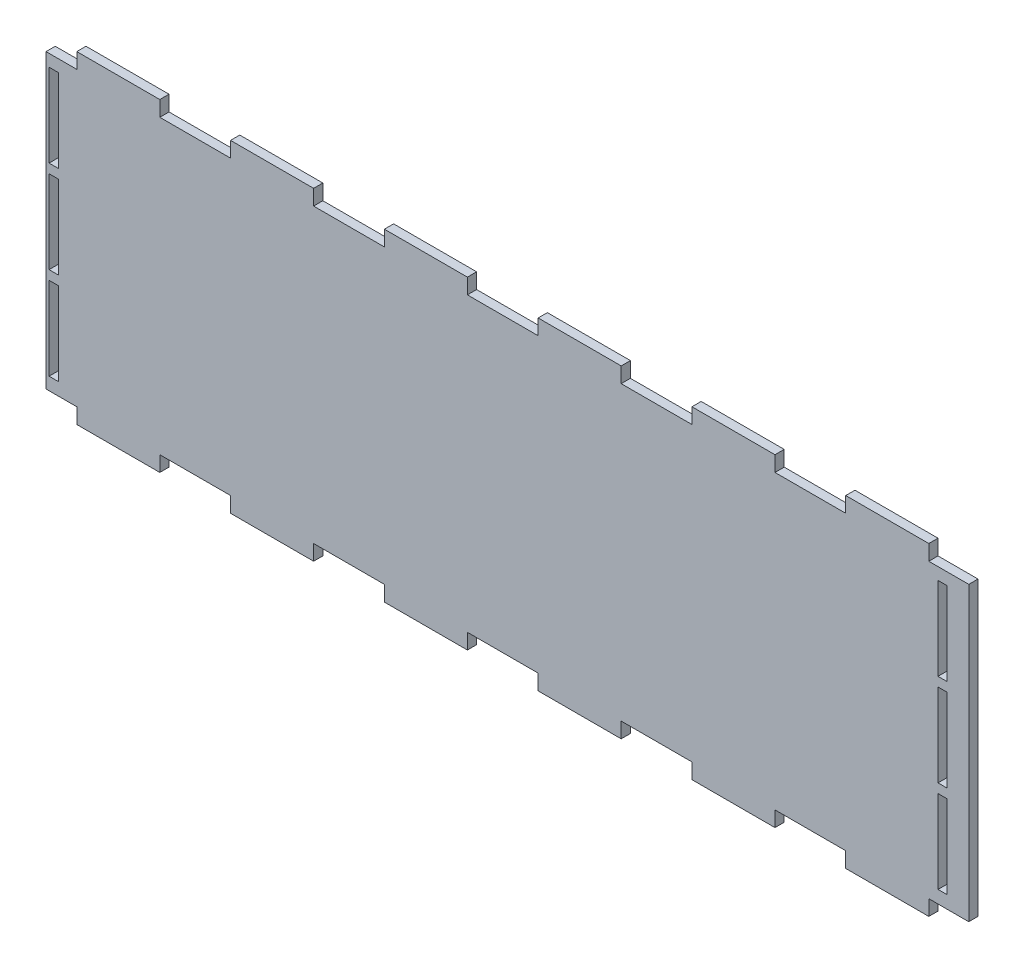
SolidWorks part; units mm, degrees
ref_plane "Plan de face" through (0, 0, 0) normal (0, 0, 1) x (1, 0, 0)
ref_plane "Plan de dessus" through (0, 0, 0) normal (0, 1, 0) x (1, 0, 0)
ref_plane "Plan de droite" through (0, 0, 0) normal (1, 0, 0) x (0, 0, -1)
sketch "Sketch1" plane through (0, 0, 0) normal (0, 0, 1) x (1, 0, 0)
  line L0 (-90, 47.5) -> (-90, 52.5)
  line L1 (150, -47.5) -> (-150, -47.5)
  line L2 (150, -47.5) -> (150, 47.5)
  line L3 (150, 47.5) -> (-150, 47.5)
  line L4 (-150, -47.5) -> (-150, 47.5)
  line L5 (150, -47.5) -> (-150, 47.5) construction
  line L6 (150, 47.5) -> (-150, -47.5) construction
  line L7 (-140, 47.5) -> (-113, 47.5)
  line L8 (-140, 47.5) -> (-140, 52.5)
  line L9 (-140, 52.5) -> (-113, 52.5)
  line L10 (-113, 47.5) -> (-113, 52.5)
  line L11 (-90, 47.5) -> (-63, 47.5)
  line L12 (-63, 47.5) -> (-63, 52.5)
  line L13 (-90, 52.5) -> (-63, 52.5)
  line L14 (-40, 47.5) -> (-40, 52.5)
  line L15 (-40, 47.5) -> (-13, 47.5)
  line L16 (-13, 47.5) -> (-13, 52.5)
  line L17 (-40, 52.5) -> (-13, 52.5)
  line L18 (10, 47.5) -> (10, 52.5)
  line L19 (10, 47.5) -> (37, 47.5)
  line L20 (37, 47.5) -> (37, 52.5)
  line L21 (10, 52.5) -> (37, 52.5)
  line L22 (60, 47.5) -> (60, 52.5)
  line L23 (60, 47.5) -> (87, 47.5)
  line L24 (87, 47.5) -> (87, 52.5)
  line L25 (60, 52.5) -> (87, 52.5)
  line L26 (110, 47.5) -> (110, 52.5)
  line L27 (110, 47.5) -> (137, 47.5)
  line L28 (137, 47.5) -> (137, 52.5)
  line L29 (110, 52.5) -> (137, 52.5)
  line L30 (-149, 13.6026) -> (-149, -13.3974)
  line L35 (-149, 43.6026) -> (-146, 43.6026)
  line L36 (-149, 43.6026) -> (-149, 16.6026)
  line L37 (-149, 16.6026) -> (-146, 16.6026)
  line L38 (-146, 43.6026) -> (-146, 16.6026)
  line L39 (-149, 13.6026) -> (-146, 13.6026)
  line L40 (-146, 13.6026) -> (-146, -13.3974)
  line L41 (-149, -13.3974) -> (-146, -13.3974)
  line L42 (-149, -16.3974) -> (-149, -43.3974)
  line L43 (-149, -16.3974) -> (-146, -16.3974)
  line L44 (-146, -16.3974) -> (-146, -43.3974)
  line L45 (-149, -43.3974) -> (-146, -43.3974)
  line L46 (-90, -47.5) -> (-90, -52.5)
  line L47 (-140, -47.5) -> (-113, -47.5)
  line L48 (-140, -47.5) -> (-140, -52.5)
  line L49 (-140, -52.5) -> (-113, -52.5)
  line L50 (-113, -47.5) -> (-113, -52.5)
  line L51 (-90, -47.5) -> (-63, -47.5)
  line L52 (-63, -47.5) -> (-63, -52.5)
  line L53 (-90, -52.5) -> (-63, -52.5)
  line L54 (-40, -47.5) -> (-40, -52.5)
  line L55 (-40, -47.5) -> (-13, -47.5)
  line L56 (-13, -47.5) -> (-13, -52.5)
  line L57 (-40, -52.5) -> (-13, -52.5)
  line L58 (10, -47.5) -> (10, -52.5)
  line L59 (10, -47.5) -> (37, -47.5)
  line L60 (37, -47.5) -> (37, -52.5)
  line L61 (10, -52.5) -> (37, -52.5)
  line L62 (60, -47.5) -> (60, -52.5)
  line L63 (60, -47.5) -> (87, -47.5)
  line L64 (87, -47.5) -> (87, -52.5)
  line L65 (60, -52.5) -> (87, -52.5)
  line L66 (110, -47.5) -> (110, -52.5)
  line L67 (110, -47.5) -> (137, -47.5)
  line L68 (137, -47.5) -> (137, -52.5)
  line L69 (110, -52.5) -> (137, -52.5)
  point P0 (0, 0)
  dimension "D1" = 300
  dimension "D2" = 95
  dimension "D3" = 10
  dimension "D4" = 5
  dimension "D5" = 27
  dimension "D7" = 27
  dimension "D8" = 3
  dimension "D9" = 1
  dimension "D10" = 3
  dimension "D11" = 27
  dimension "D12" = 5
  dimension "D13" = 10
  dimension "D6" = 6
  dimension "D14" = 6
extrude "Boss-Extrude1" add sketch "Sketch1" along normal blind 3 contours L4 L1 L2 L3 | L3 L10 L9 L8 | L13 L0 L3 L12 | L17 L14 L3 L16 | L21 L18 L3 L20 | L25 L24 L23 L22 | L29 L28 L27 L26
sketch "Sketch2" plane through (0, 0, 3) normal (0, 0, 1) x (1, 0, 0)
  line L1 (140, 43.6) -> (143, 43.6)
  line L2 (140, 43.6) -> (140, 16.6)
  line L3 (140, 16.6) -> (143, 16.6)
  line L4 (143, 43.6) -> (143, 16.6)
  line L5 (150, 47.5) -> (137, 47.5) construction
  line L6 (140, 13.6) -> (140, -13.4)
  line L7 (140, 13.6) -> (143, 13.6)
  line L8 (143, 13.6) -> (143, -13.4)
  line L9 (140, -13.4) -> (143, -13.4)
  line L10 (140, -16.4) -> (140, -43.4)
  line L11 (140, -16.4) -> (143, -16.4)
  line L12 (143, -16.4) -> (143, -43.4)
  line L13 (140, -43.4) -> (143, -43.4)
  line L15 (150, -47.5) -> (150, 47.5) construction
  dimension "D1" = 7
  dimension "D2" = 3.9
  dimension "D3" = 27
  dimension "D4" = 3
  dimension "D5" = 3
extrude "Cut-Extrude1" cut sketch "Sketch2" against normal blind 10
sketch "Sketch3" plane through (0, 0, 3) normal (0, 0, 1) x (1, 0, 0)
  line L0 (150, -47.5) -> (-150, -47.5) construction
  line L1 (-140, -47.5) -> (-113, -47.5)
  line L2 (-140, -47.5) -> (-140, -52.5)
  line L3 (-140, -52.5) -> (-113, -52.5)
  line L4 (-113, -47.5) -> (-113, -52.5)
  line L5 (-150, -47.5) -> (-150, 47.5) construction
  line L6 (-90, -47.5) -> (-90, -52.5)
  line L7 (-90, -47.5) -> (-63, -47.5)
  line L8 (-63, -47.5) -> (-63, -52.5)
  line L9 (-90, -52.5) -> (-63, -52.5)
  line L10 (-40, -47.5) -> (-40, -52.5)
  line L11 (-40, -47.5) -> (-13, -47.5)
  line L12 (-13, -47.5) -> (-13, -52.5)
  line L13 (-40, -52.5) -> (-13, -52.5)
  line L14 (10, -47.5) -> (10, -52.5)
  line L15 (10, -47.5) -> (37, -47.5)
  line L16 (37, -47.5) -> (37, -52.5)
  line L17 (10, -52.5) -> (37, -52.5)
  line L18 (60, -47.5) -> (60, -52.5)
  line L19 (60, -47.5) -> (87, -47.5)
  line L20 (87, -47.5) -> (87, -52.5)
  line L21 (60, -52.5) -> (87, -52.5)
  line L22 (110, -47.5) -> (110, -52.5)
  line L23 (110, -47.5) -> (137, -47.5)
  line L24 (137, -47.5) -> (137, -52.5)
  line L25 (110, -52.5) -> (137, -52.5)
  dimension "D1" = 10
  dimension "D2" = 27
  dimension "D3" = 5
  dimension "D4" = 6
extrude "Boss-Extrude3" add sketch "Sketch3" against normal blind 3
